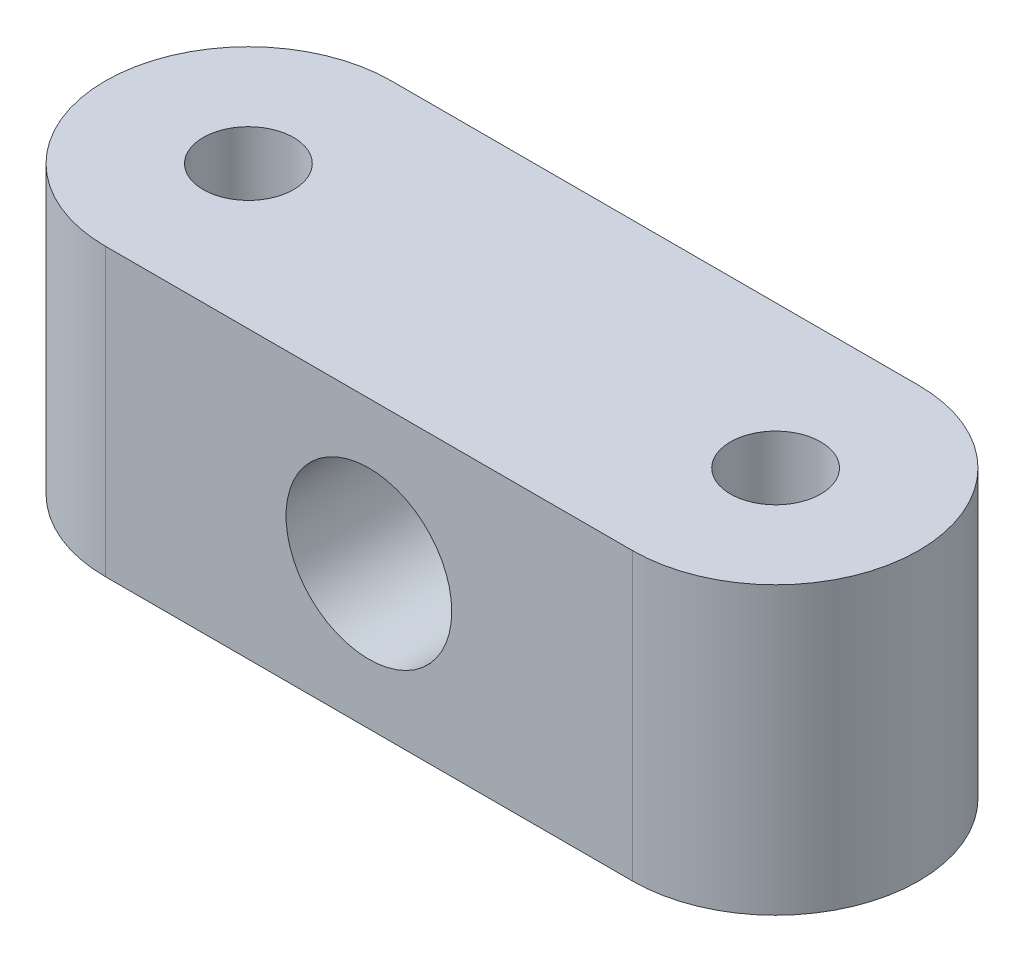
SolidWorks part; units mm, degrees
ref_plane "Front Plane" through (0, 0, 0) normal (0, 0, 1) x (1, 0, 0)
ref_plane "Top Plane" through (0, 0, 0) normal (0, 1, 0) x (1, 0, 0)
ref_plane "Right Plane" through (0, 0, 0) normal (1, 0, 0) x (0, 0, -1)
sketch "Sketch2" plane through (0, 0, 0) normal (0, 1, 0) x (1, 0, 0)
  line L0 (0, 0) -> (0, 24.4937) construction
  line L1 (0, 0) -> (27.8817, 0) construction
  line L2 (-35, 19) -> (35, 19)
  line L3 (-35, -19) -> (35, -19)
  arc A0 (-35, 19) -> (-35, -19) centre (-35, 0) ccw
  circle A1 centre (-35, 0) radius 6
  circle A2 centre (35, 0) radius 6
  arc A3 (35, 19) -> (35, -19) centre (35, 0) cw
  dimension "D1" = 38
  dimension "D2" = 12
  dimension "D3" = 35
extrude "Boss-Extrude1" add sketch "Sketch2" along normal blind 38
hole_wizard "M24x2.0 Tapped Hole1" positions "Sketch4" profile "Sketch5" tap size "M24x2.0" standard "ANSI Metric"
sketch "Sketch4" plane through (0, 0, 19) normal (0, 0, 1) x (1, 0, 0)
  line L0 (-35, 38) -> (35, 38) construction
  line L1 (35, 38) -> (35, 0) construction
  point P0 (0, 19)
  point P9 (33.0319, 14.73)
  point P12 (0, 0)
  dimension "D1" = 19
  dimension "D2" = 35
sketch "Sketch5" plane through (0, 19, 19) normal (1, 0, 0) x (0, -1, 0)
  line L0 (0, 0) -> (0, 44.6095)
  line L1 (0, 44.6095) -> (11, 38)
  line L2 (11, 38) -> (11, 0)
  line L5 (11, 0) -> (0, 0)
  line L10 (0, 44.6095) -> (-11, 38) construction
  line L11 (0, -6.35) -> (0, 107.95) construction
  dimension "Tap Drill Dia." = 22
  dimension "Tap Drill Depth" = 38
  dimension "Drill Angle" = 118
